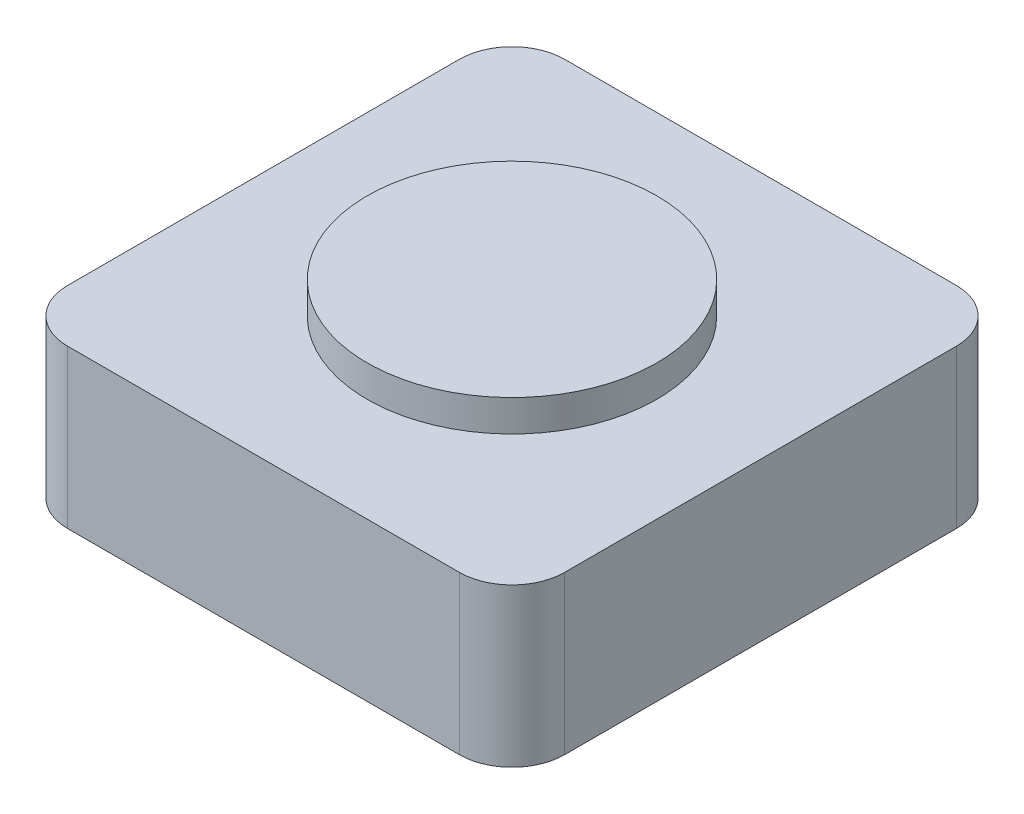
SolidWorks part; units mm, degrees
ref_plane "Front Plane" through (0, 0, 0) normal (0, 0, 1) x (1, 0, 0)
ref_plane "Top Plane" through (0, 0, 0) normal (0, 1, 0) x (1, 0, 0)
ref_plane "Right Plane" through (0, 0, 0) normal (1, 0, 0) x (0, 0, -1)
sketch "Sketch1" plane through (0, 0, 0) normal (0, 1, 0) x (1, 0, 0)
  line L1 (-5.9944, -5.9944) -> (5.9944, -5.9944)
  line L2 (-5.9944, -5.9944) -> (-5.9944, 5.9944)
  line L3 (-5.9944, 5.9944) -> (5.9944, 5.9944)
  line L4 (5.9944, -5.9944) -> (5.9944, 5.9944)
  line L5 (-5.9944, -5.9944) -> (5.9944, 5.9944) construction
  line L6 (-5.9944, 5.9944) -> (5.9944, -5.9944) construction
  point P0 (0, 0)
  dimension "D1" = 11.9888
  dimension "D2" = 11.9888
extrude "Boss-Extrude1" add sketch "Sketch1" along normal blind 3.81
sketch "Sketch2" plane through (0, 3.81, 0) normal (0, 1, 0) x (1, 0, 0)
  circle A0 centre (0, 0) radius 3.4925
  dimension "D1" = 6.985
extrude "Boss-Extrude2" add sketch "Sketch2" along normal blind 0.762
fillet "Fillet3" radius 1.27 4 edges at (5.9944, 1.905, 5.9944) (-5.9944, 1.905, 5.9944) (5.9944, 1.905, -5.9944) (-5.9944, 1.905, -5.9944)
